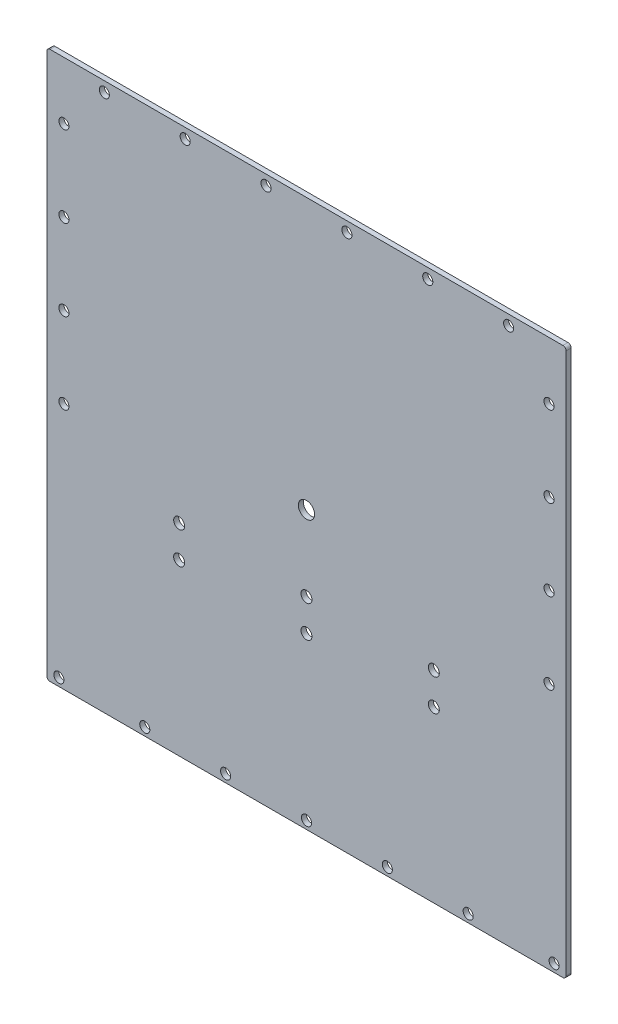
SolidWorks part; units mm, degrees
material "6061 Alloy"
ref_plane "Front Plane" through (0, 0, 0) normal (0, 0, 1) x (1, 0, 0)
ref_plane "Top Plane" through (0, 0, 0) normal (0, 1, 0) x (1, 0, 0)
ref_plane "Right Plane" through (0, 0, 0) normal (1, 0, 0) x (0, 0, -1)
sketch "Sketch2" plane through (0, 0, 0) normal (0, 0, 1) x (1, 0, 0)
  line L0 (0, -176.7623) -> (165.1, -176.7623)
  line L1 (0, 0) -> (165.1, 0)
  line L5 (82.55, 0) -> (82.55, -176.7623) construction
  line L6 (165.1, 0) -> (165.1, -176.7623)
  line L7 (0, 0) -> (0, -176.7623)
  line L8 (0, 0) -> (0, -176.7623)
  line L9 (0, -171.98) -> (165.1, -171.98)
  line L10 (1, 0) -> (1, -171.98)
  line L11 (164.1, -171.98) -> (164.1, 0)
  circle A31 centre (31.75, -169.48) radius 1.5875
  circle A32 centre (57.15, -169.48) radius 1.5875
  circle A33 centre (82.55, -169.48) radius 1.5875
  circle A34 centre (107.95, -169.48) radius 1.5875
  circle A35 centre (133.35, -169.48) radius 1.5875
  circle A63 centre (6.35, -18.05) radius 1.5875
  circle A65 centre (160.3375, -169.48) radius 1.5875
  circle A66 centre (4.7625, -169.48) radius 1.5875
  circle A67 centre (82.55, -85) radius 2.5527
  circle A69 centre (19.05, -3.175) radius 1.5875
  circle A70 centre (44.45, -3.175) radius 1.5875
  circle A71 centre (69.85, -3.175) radius 1.5875
  circle A72 centre (95.25, -3.175) radius 1.5875
  circle A73 centre (120.65, -3.175) radius 1.5875
  circle A74 centre (146.05, -3.175) radius 1.5875
  circle A76 centre (6.35, -43.45) radius 1.5875
  circle A77 centre (6.35, -68.85) radius 1.5875
  circle A78 centre (6.35, -94.25) radius 1.5875
  circle A81 centre (158.75, -68.85) radius 1.5875
  circle A82 centre (158.75, -94.25) radius 1.5875
  circle A83 centre (158.75, -43.45) radius 1.5875
  circle A84 centre (158.75, -18.05) radius 1.5875
  dimension "D9" = 3.175
  dimension "D4" = 3.175
  dimension "D21" = 5.1054
  dimension "D1" = 165.1
  dimension "D23" = 25.4
  dimension "D5" = 176.7623
  dimension "D8" = 31.75
  dimension "D11" = 7.2823
  dimension "D10" = 19.05
  dimension "D12" = 3.175
  dimension "D14" = 25.4
  dimension "D3" = 18.05
  dimension "D6" = 6.35
  dimension "D15" = 25.4
  dimension "D16" = 2.5
  dimension "D17" = 4.7625
  dimension "D18" = 1
  dimension "D19" = 1
  dimension "D20" = 85
  dimension "D22" = 5
  dimension "D13" = 3
  dimension "D7" = 4
extrude "Boss-Extrude2" add sketch "Sketch2" along normal blind 1.5875
fillet "Fillet1" radius 1 4 edges at (1, -171.98, 0.7937) (1, 0, 0.7937) (164.1, 0, 0.7937) (164.1, -171.98, 0.7937)
sketch "Sketch3" plane through (0, 0, 1.5875) normal (0, 0, 1) x (1, 0, 0)
  line L0 (2, -171.98) -> (163.1, -171.98) construction
  line L2 (1, -1) -> (1, -170.98) construction
  circle A0 centre (42.55, -108.6304) radius 1.725
  circle A1 centre (82.55, -108.6304) radius 1.725
  circle A2 centre (122.55, -108.6304) radius 1.725
  circle A3 centre (42.55, -118.6304) radius 1.725
  circle A4 centre (82.55, -118.6304) radius 1.725
  circle A5 centre (122.55, -118.6304) radius 1.725
  dimension "D4" = 3.45
  dimension "D1" = 40
  dimension "D2" = 40
  dimension "D3" = 63.3496
  dimension "D5" = 41.55
  dimension "D6" = 10
extrude "Cut-Extrude1" cut sketch "Sketch3" against normal through all both and the other way through all
equation "\"D19@Sketch2\"=\"D18@Sketch2\""
equation "\"D9@Sketch2\"=\"D4@Sketch2\""
